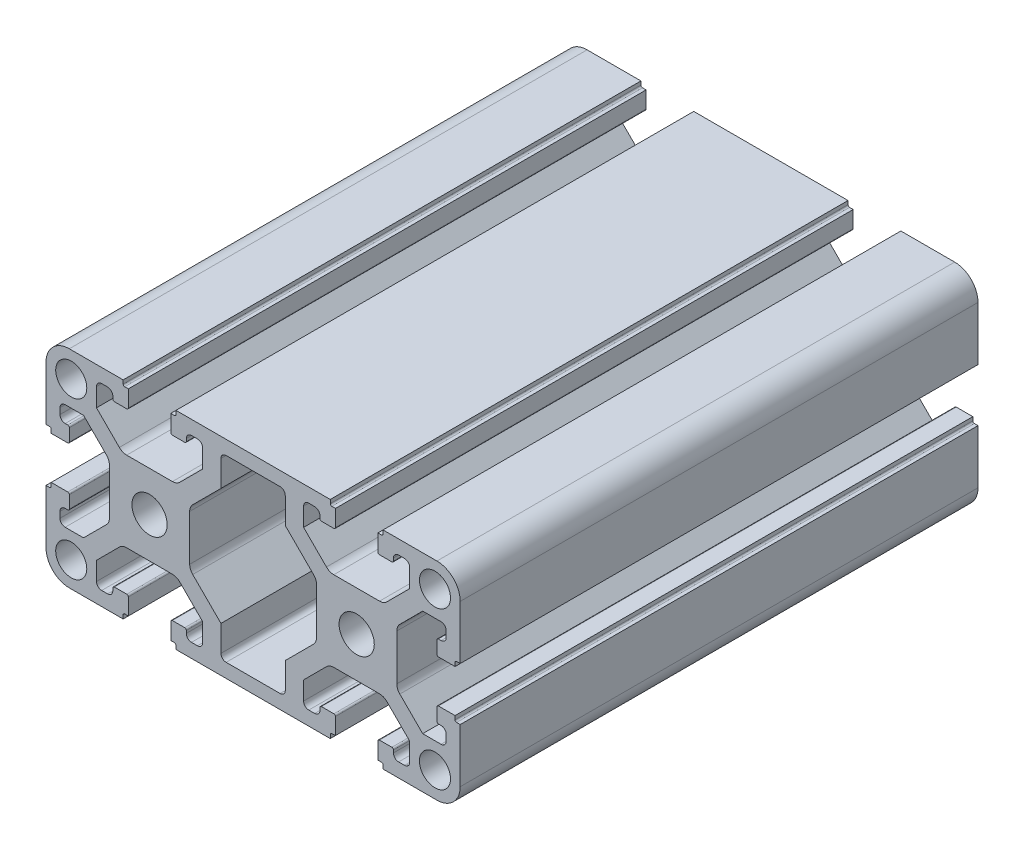
SolidWorks part; units mm, degrees
ref_plane "前视基准面" through (0, 0, 0) normal (0, 0, 1) x (1, 0, 0)
ref_plane "上视基准面" through (0, 0, 0) normal (0, 1, 0) x (1, 0, 0)
ref_plane "右视基准面" through (0, 0, 0) normal (1, 0, 0) x (0, 0, -1)
sketch "草图1" plane through (0, 0, 0) normal (0, 0, 1) x (1, 0, 0)
  line L0 (-25.8856, 19.8486) -> (-36.2856, 19.8486)
  line L1 (-40.7856, 15.3486) -> (-40.7856, 4.9486)
  line L2 (-33.5388, 10.0986) -> (-37.0856, 10.0986)
  line L3 (-38.0856, 9.0986) -> (-38.0856, 7.9486)
  line L4 (-37.0856, 6.9486) -> (-36.5856, 6.9486)
  line L5 (-36.2856, 6.6486) -> (-36.2856, 4.2486)
  line L6 (-36.5856, 3.9486) -> (-39.7856, 3.9486)
  line L7 (14.1144, -20.1514) -> (-5.2856, -20.1514)
  line L8 (-40.7856, 4.9486) -> (-40.0856, 4.9486)
  line L9 (-39.7856, 4.6486) -> (-39.7856, 3.9486)
  line L10 (-33.5388, 10.0986) -> (-29.1214, 5.6812)
  line L11 (-28.5356, 4.267) -> (-28.5356, -4.5698)
  line L12 (-29.1214, -5.984) -> (-33.5388, -10.4014)
  line L13 (-31.0356, -12.9046) -> (-26.6182, -8.4872)
  line L14 (-25.204, -7.9014) -> (-16.3672, -7.9014)
  line L15 (-14.953, -8.4872) -> (-10.5356, -12.9046)
  line L16 (-6.9956, -11.4382) -> (-12.4498, -5.984)
  line L17 (-13.0356, -4.5698) -> (-13.0356, 4.267)
  line L18 (-12.4498, 5.6812) -> (-6.9956, 11.1354)
  line L19 (-10.5356, 12.6018) -> (-14.953, 8.1844)
  line L20 (-16.3672, 7.5986) -> (-25.204, 7.5986)
  line L21 (-26.6182, 8.1844) -> (-31.0356, 12.6018)
  line L22 (-25.8856, 19.8486) -> (-25.8856, 19.1486)
  line L23 (-25.5856, 18.8486) -> (-24.8856, 18.8486)
  line L24 (-31.0356, 12.6018) -> (-31.0356, 16.1486)
  line L25 (-30.0356, 17.1486) -> (-28.8856, 17.1486)
  line L26 (-27.8856, 16.1486) -> (-27.8856, 15.6486)
  line L27 (-27.5856, 15.3486) -> (-25.1856, 15.3486)
  line L28 (-24.8856, 15.6486) -> (-24.8856, 18.8486)
  line L29 (-15.6856, 19.8486) -> (-5.2856, 19.8486)
  line L31 (-10.5356, 12.6018) -> (-10.5356, 16.1486)
  line L32 (-11.5356, 17.1486) -> (-12.6856, 17.1486)
  line L33 (-13.6856, 16.1486) -> (-13.6856, 15.6486)
  line L34 (-13.9856, 15.3486) -> (-16.3856, 15.3486)
  line L35 (-16.6856, 15.6486) -> (-16.6856, 18.8486)
  line L36 (-15.6856, 19.8486) -> (-15.6856, 19.1486)
  line L37 (-15.9856, 18.8486) -> (-16.6856, 18.8486)
  line L38 (-25.8856, -20.1514) -> (-36.2856, -20.1514)
  line L39 (-40.7856, -15.6514) -> (-40.7856, -5.2514)
  line L41 (-33.5388, -10.4014) -> (-37.0856, -10.4014)
  line L42 (-38.0856, -9.4014) -> (-38.0856, -8.2514)
  line L43 (-37.0856, -7.2514) -> (-36.5856, -7.2514)
  line L44 (-36.2856, -6.9514) -> (-36.2856, -4.5514)
  line L45 (-36.5856, -4.2514) -> (-39.7856, -4.2514)
  line L46 (-40.7856, -5.2514) -> (-40.0856, -5.2514)
  line L47 (-39.7856, -4.9514) -> (-39.7856, -4.2514)
  line L48 (-31.0356, -12.9046) -> (-31.0356, -16.4514)
  line L49 (-30.0356, -17.4514) -> (-28.8856, -17.4514)
  line L50 (-27.8856, -16.4514) -> (-27.8856, -15.9514)
  line L51 (-27.5856, -15.6514) -> (-25.1856, -15.6514)
  line L52 (-24.8856, -15.9514) -> (-24.8856, -19.1514)
  line L53 (-25.8856, -20.1514) -> (-25.8856, -19.4514)
  line L54 (-25.5856, -19.1514) -> (-24.8856, -19.1514)
  line L55 (-15.6856, -20.1514) -> (-5.2856, -20.1514)
  line L57 (-10.5356, -12.9046) -> (-10.5356, -16.4514)
  line L58 (-11.5356, -17.4514) -> (-12.6856, -17.4514)
  line L59 (-13.6856, -16.4514) -> (-13.6856, -15.9514)
  line L60 (-13.9856, -15.6514) -> (-16.3856, -15.6514)
  line L61 (-16.6856, -15.9514) -> (-16.6856, -19.1514)
  line L62 (-15.6856, -20.1514) -> (-15.6856, -19.4514)
  line L63 (-15.9856, -19.1514) -> (-16.6856, -19.1514)
  line L64 (14.1144, 19.8486) -> (3.7144, 19.8486)
  line L66 (5.4244, 11.1354) -> (10.8786, 5.6812)
  line L67 (11.4644, 4.267) -> (11.4644, -4.5698)
  line L68 (10.8786, -5.984) -> (5.4244, -11.4382)
  line L69 (8.9644, -12.9046) -> (13.3818, -8.4872)
  line L70 (14.796, -7.9014) -> (23.6328, -7.9014)
  line L71 (25.047, -8.4872) -> (29.4644, -12.9046)
  line L72 (31.9675, -10.4014) -> (27.5502, -5.984)
  line L73 (26.9644, -4.5698) -> (26.9644, 4.267)
  line L74 (27.5502, 5.6812) -> (31.9675, 10.0986)
  line L75 (29.4644, 12.6018) -> (25.047, 8.1844)
  line L76 (23.6328, 7.5986) -> (14.796, 7.5986)
  line L77 (13.3818, 8.1844) -> (8.9644, 12.6018)
  line L78 (14.1144, 19.8486) -> (14.1144, 19.1486)
  line L79 (14.4144, 18.8486) -> (15.1144, 18.8486)
  line L80 (8.9644, 12.6018) -> (8.9644, 16.1486)
  line L81 (9.9644, 17.1486) -> (11.1144, 17.1486)
  line L82 (12.1144, 16.1486) -> (12.1144, 15.6486)
  line L83 (12.4144, 15.3486) -> (14.8144, 15.3486)
  line L84 (15.1144, 15.6486) -> (15.1144, 18.8486)
  line L85 (24.3144, 19.8486) -> (34.7144, 19.8486)
  line L86 (39.2144, 15.3486) -> (39.2144, 4.9486)
  line L87 (31.9675, 10.0986) -> (35.5144, 10.0986)
  line L88 (36.5144, 9.0986) -> (36.5144, 7.9486)
  line L89 (35.5144, 6.9486) -> (35.0144, 6.9486)
  line L90 (34.7144, 6.6486) -> (34.7144, 4.2486)
  line L91 (35.0144, 3.9486) -> (38.2144, 3.9486)
  line L93 (39.2144, 4.9486) -> (38.5144, 4.9486)
  line L94 (38.2144, 4.6486) -> (38.2144, 3.9486)
  line L95 (29.4644, 12.6018) -> (29.4644, 16.1486)
  line L96 (28.4644, 17.1486) -> (27.3144, 17.1486)
  line L97 (26.3144, 16.1486) -> (26.3144, 15.6486)
  line L98 (26.0144, 15.3486) -> (23.6144, 15.3486)
  line L99 (23.3144, 15.6486) -> (23.3144, 18.8486)
  line L100 (24.3144, 19.8486) -> (24.3144, 19.1486)
  line L101 (24.0144, 18.8486) -> (23.3144, 18.8486)
  line L104 (8.9644, -12.9046) -> (8.9644, -16.4514)
  line L105 (9.9644, -17.4514) -> (11.1144, -17.4514)
  line L106 (12.1144, -16.4514) -> (12.1144, -15.9514)
  line L107 (12.4144, -15.6514) -> (14.8144, -15.6514)
  line L108 (15.1144, -15.9514) -> (15.1144, -19.1514)
  line L109 (14.1144, -20.1514) -> (14.1144, -19.4514)
  line L110 (14.4144, -19.1514) -> (15.1144, -19.1514)
  line L111 (24.3144, -20.1514) -> (34.7144, -20.1514)
  line L112 (39.2144, -15.6514) -> (39.2144, -5.2514)
  line L114 (31.9675, -10.4014) -> (35.5144, -10.4014)
  line L115 (36.5144, -9.4014) -> (36.5144, -8.2514)
  line L116 (35.5144, -7.2514) -> (35.0144, -7.2514)
  line L117 (34.7144, -6.9514) -> (34.7144, -4.5514)
  line L118 (35.0144, -4.2514) -> (38.2144, -4.2514)
  line L119 (39.2144, -5.2514) -> (38.5144, -5.2514)
  line L120 (38.2144, -4.9514) -> (38.2144, -4.2514)
  line L121 (29.4644, -12.9046) -> (29.4644, -16.4514)
  line L122 (28.4644, -17.4514) -> (27.3144, -17.4514)
  line L123 (26.3144, -16.4514) -> (26.3144, -15.9514)
  line L124 (26.0144, -15.6514) -> (23.6144, -15.6514)
  line L125 (23.3144, -15.9514) -> (23.3144, -19.1514)
  line L126 (24.3144, -20.1514) -> (24.3144, -19.4514)
  line L127 (24.0144, -19.1514) -> (23.3144, -19.1514)
  line L129 (-5.2856, 19.8486) -> (3.7144, 19.8486)
  line L131 (-6.9956, 11.1354) -> (-6.9956, 16.1486)
  line L132 (-5.9956, 17.1486) -> (4.4244, 17.1486)
  line L133 (5.4244, 11.1354) -> (5.4244, 16.1486)
  line L134 (-6.9956, -11.4382) -> (-6.9956, -16.4514)
  line L135 (-5.9956, -17.4514) -> (4.4244, -17.4514)
  line L136 (5.4244, -11.4382) -> (5.4244, -16.4514)
  arc A0 (-36.2856, 19.8486) -> (-40.7856, 15.3486) centre (-36.2856, 15.3486) ccw
  arc A1 (-37.0856, 10.0986) -> (-38.0856, 9.0986) centre (-37.0856, 9.0986) ccw
  arc A2 (-38.0856, 7.9486) -> (-37.0856, 6.9486) centre (-37.0856, 7.9486) ccw
  arc A3 (-36.2856, 6.6486) -> (-36.5856, 6.9486) centre (-36.5856, 6.6486) ccw
  arc A4 (-36.5856, 3.9486) -> (-36.2856, 4.2486) centre (-36.5856, 4.2486) ccw
  arc A5 (-39.7856, 4.6486) -> (-40.0856, 4.9486) centre (-40.0856, 4.6486) ccw
  arc A6 (-28.5356, 4.267) -> (-29.1214, 5.6812) centre (-30.5356, 4.267) ccw
  arc A7 (-29.1214, -5.984) -> (-28.5356, -4.5698) centre (-30.5356, -4.5698) ccw
  arc A8 (-25.204, -7.9014) -> (-26.6182, -8.4872) centre (-25.204, -9.9014) ccw
  arc A9 (-14.953, -8.4872) -> (-16.3672, -7.9014) centre (-16.3672, -9.9014) ccw
  arc A10 (-13.0356, -4.5698) -> (-12.4498, -5.984) centre (-11.0356, -4.5698) ccw
  arc A11 (-12.4498, 5.6812) -> (-13.0356, 4.267) centre (-11.0356, 4.267) ccw
  arc A12 (-16.3672, 7.5986) -> (-14.953, 8.1844) centre (-16.3672, 9.5986) ccw
  arc A13 (-26.6182, 8.1844) -> (-25.204, 7.5986) centre (-25.204, 9.5986) ccw
  circle A14 centre (-20.7856, -0.1514) radius 3.4
  circle A15 centre (-35.9106, 14.9736) radius 3
  arc A16 (-25.8856, 19.1486) -> (-25.5856, 18.8486) centre (-25.5856, 19.1486) ccw
  arc A17 (-30.0356, 17.1486) -> (-31.0356, 16.1486) centre (-30.0356, 16.1486) ccw
  arc A18 (-27.8856, 16.1486) -> (-28.8856, 17.1486) centre (-28.8856, 16.1486) ccw
  arc A19 (-27.8856, 15.6486) -> (-27.5856, 15.3486) centre (-27.5856, 15.6486) ccw
  arc A20 (-25.1856, 15.3486) -> (-24.8856, 15.6486) centre (-25.1856, 15.6486) ccw
  arc A21 (-10.5356, 16.1486) -> (-11.5356, 17.1486) centre (-11.5356, 16.1486) ccw
  arc A22 (-12.6856, 17.1486) -> (-13.6856, 16.1486) centre (-12.6856, 16.1486) ccw
  arc A23 (-13.9856, 15.3486) -> (-13.6856, 15.6486) centre (-13.9856, 15.6486) ccw
  arc A24 (-16.6856, 15.6486) -> (-16.3856, 15.3486) centre (-16.3856, 15.6486) ccw
  arc A25 (-15.9856, 18.8486) -> (-15.6856, 19.1486) centre (-15.9856, 19.1486) ccw
  arc A26 (-40.7856, -15.6514) -> (-36.2856, -20.1514) centre (-36.2856, -15.6514) ccw
  arc A27 (-38.0856, -9.4014) -> (-37.0856, -10.4014) centre (-37.0856, -9.4014) ccw
  arc A28 (-37.0856, -7.2514) -> (-38.0856, -8.2514) centre (-37.0856, -8.2514) ccw
  arc A29 (-36.5856, -7.2514) -> (-36.2856, -6.9514) centre (-36.5856, -6.9514) ccw
  arc A30 (-36.2856, -4.5514) -> (-36.5856, -4.2514) centre (-36.5856, -4.5514) ccw
  arc A31 (-40.0856, -5.2514) -> (-39.7856, -4.9514) centre (-40.0856, -4.9514) ccw
  circle A32 centre (-35.9106, -15.2764) radius 3
  arc A33 (-31.0356, -16.4514) -> (-30.0356, -17.4514) centre (-30.0356, -16.4514) ccw
  arc A34 (-28.8856, -17.4514) -> (-27.8856, -16.4514) centre (-28.8856, -16.4514) ccw
  arc A35 (-27.5856, -15.6514) -> (-27.8856, -15.9514) centre (-27.5856, -15.9514) ccw
  arc A36 (-24.8856, -15.9514) -> (-25.1856, -15.6514) centre (-25.1856, -15.9514) ccw
  arc A37 (-25.5856, -19.1514) -> (-25.8856, -19.4514) centre (-25.5856, -19.4514) ccw
  arc A38 (-11.5356, -17.4514) -> (-10.5356, -16.4514) centre (-11.5356, -16.4514) ccw
  arc A39 (-13.6856, -16.4514) -> (-12.6856, -17.4514) centre (-12.6856, -16.4514) ccw
  arc A40 (-13.6856, -15.9514) -> (-13.9856, -15.6514) centre (-13.9856, -15.9514) ccw
  arc A41 (-16.3856, -15.6514) -> (-16.6856, -15.9514) centre (-16.3856, -15.9514) ccw
  arc A42 (-15.6856, -19.4514) -> (-15.9856, -19.1514) centre (-15.9856, -19.4514) ccw
  arc A43 (11.4644, 4.267) -> (10.8786, 5.6812) centre (9.4644, 4.267) ccw
  arc A44 (10.8786, -5.984) -> (11.4644, -4.5698) centre (9.4644, -4.5698) ccw
  arc A45 (14.796, -7.9014) -> (13.3818, -8.4872) centre (14.796, -9.9014) ccw
  arc A46 (25.047, -8.4872) -> (23.6328, -7.9014) centre (23.6328, -9.9014) ccw
  arc A47 (26.9644, -4.5698) -> (27.5502, -5.984) centre (28.9644, -4.5698) ccw
  arc A48 (27.5502, 5.6812) -> (26.9644, 4.267) centre (28.9644, 4.267) ccw
  arc A49 (23.6328, 7.5986) -> (25.047, 8.1844) centre (23.6328, 9.5986) ccw
  arc A50 (13.3818, 8.1844) -> (14.796, 7.5986) centre (14.796, 9.5986) ccw
  circle A51 centre (19.2144, -0.1514) radius 3.4
  arc A52 (14.1144, 19.1486) -> (14.4144, 18.8486) centre (14.4144, 19.1486) ccw
  arc A53 (9.9644, 17.1486) -> (8.9644, 16.1486) centre (9.9644, 16.1486) ccw
  arc A54 (12.1144, 16.1486) -> (11.1144, 17.1486) centre (11.1144, 16.1486) ccw
  arc A55 (12.1144, 15.6486) -> (12.4144, 15.3486) centre (12.4144, 15.6486) ccw
  arc A56 (14.8144, 15.3486) -> (15.1144, 15.6486) centre (14.8144, 15.6486) ccw
  arc A57 (39.2144, 15.3486) -> (34.7144, 19.8486) centre (34.7144, 15.3486) ccw
  arc A58 (36.5144, 9.0986) -> (35.5144, 10.0986) centre (35.5144, 9.0986) ccw
  arc A59 (35.5144, 6.9486) -> (36.5144, 7.9486) centre (35.5144, 7.9486) ccw
  arc A60 (35.0144, 6.9486) -> (34.7144, 6.6486) centre (35.0144, 6.6486) ccw
  arc A61 (34.7144, 4.2486) -> (35.0144, 3.9486) centre (35.0144, 4.2486) ccw
  arc A62 (38.5144, 4.9486) -> (38.2144, 4.6486) centre (38.5144, 4.6486) ccw
  circle A63 centre (34.3394, 14.9736) radius 3
  arc A64 (29.4644, 16.1486) -> (28.4644, 17.1486) centre (28.4644, 16.1486) ccw
  arc A65 (27.3144, 17.1486) -> (26.3144, 16.1486) centre (27.3144, 16.1486) ccw
  arc A66 (26.0144, 15.3486) -> (26.3144, 15.6486) centre (26.0144, 15.6486) ccw
  arc A67 (23.3144, 15.6486) -> (23.6144, 15.3486) centre (23.6144, 15.6486) ccw
  arc A68 (24.0144, 18.8486) -> (24.3144, 19.1486) centre (24.0144, 19.1486) ccw
  arc A69 (8.9644, -16.4514) -> (9.9644, -17.4514) centre (9.9644, -16.4514) ccw
  arc A70 (11.1144, -17.4514) -> (12.1144, -16.4514) centre (11.1144, -16.4514) ccw
  arc A71 (12.4144, -15.6514) -> (12.1144, -15.9514) centre (12.4144, -15.9514) ccw
  arc A72 (15.1144, -15.9514) -> (14.8144, -15.6514) centre (14.8144, -15.9514) ccw
  arc A73 (14.4144, -19.1514) -> (14.1144, -19.4514) centre (14.4144, -19.4514) ccw
  arc A74 (34.7144, -20.1514) -> (39.2144, -15.6514) centre (34.7144, -15.6514) ccw
  arc A75 (35.5144, -10.4014) -> (36.5144, -9.4014) centre (35.5144, -9.4014) ccw
  arc A76 (36.5144, -8.2514) -> (35.5144, -7.2514) centre (35.5144, -8.2514) ccw
  arc A77 (34.7144, -6.9514) -> (35.0144, -7.2514) centre (35.0144, -6.9514) ccw
  arc A78 (35.0144, -4.2514) -> (34.7144, -4.5514) centre (35.0144, -4.5514) ccw
  arc A79 (38.2144, -4.9514) -> (38.5144, -5.2514) centre (38.5144, -4.9514) ccw
  circle A80 centre (34.3394, -15.2764) radius 3
  arc A81 (28.4644, -17.4514) -> (29.4644, -16.4514) centre (28.4644, -16.4514) ccw
  arc A82 (26.3144, -16.4514) -> (27.3144, -17.4514) centre (27.3144, -16.4514) ccw
  arc A83 (26.3144, -15.9514) -> (26.0144, -15.6514) centre (26.0144, -15.9514) ccw
  arc A84 (23.6144, -15.6514) -> (23.3144, -15.9514) centre (23.6144, -15.9514) ccw
  arc A85 (24.3144, -19.4514) -> (24.0144, -19.1514) centre (24.0144, -19.4514) ccw
  arc A86 (-5.9956, 17.1486) -> (-6.9956, 16.1486) centre (-5.9956, 16.1486) ccw
  arc A87 (5.4244, 16.1486) -> (4.4244, 17.1486) centre (4.4244, 16.1486) ccw
  arc A88 (-6.9956, -16.4514) -> (-5.9956, -17.4514) centre (-5.9956, -16.4514) ccw
  arc A89 (4.4244, -17.4514) -> (5.4244, -16.4514) centre (4.4244, -16.4514) ccw
extrude "凸台-拉伸1" add sketch "草图1" along normal blind 100
